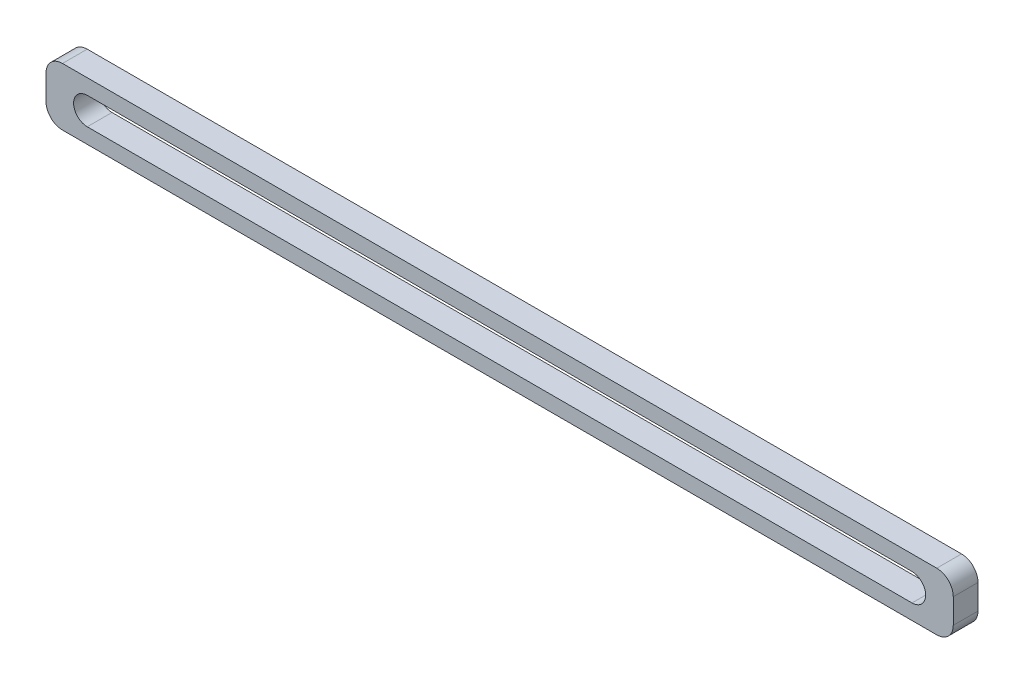
SolidWorks part; units mm, degrees
ref_plane "前视基准面" through (0, 0, 0) normal (0, 0, 1) x (1, 0, 0)
ref_plane "上视基准面" through (0, 0, 0) normal (0, 1, 0) x (1, 0, 0)
ref_plane "右视基准面" through (0, 0, 0) normal (1, 0, 0) x (0, 0, -1)
sketch "草图1" plane through (0, 0, 0) normal (0, 0, 1) x (1, 0, 0)
  line L0 (-50, 0) -> (50, 0) construction
  line L1 (-55, 3.5) -> (55, 3.5)
  line L2 (-55, 3.5) -> (-55, -3.5)
  line L3 (-55, -3.5) -> (55, -3.5)
  line L4 (55, 3.5) -> (55, -3.5)
  line L5 (-55, 3.5) -> (55, -3.5) construction
  line L6 (-55, -3.5) -> (55, 3.5) construction
  line L7 (-50, 1.65) -> (50, 1.65)
  line L8 (-50, -1.65) -> (50, -1.65)
  arc A0 (-50, 1.65) -> (-50, -1.65) centre (-50, 0) ccw
  arc A1 (50, -1.65) -> (50, 1.65) centre (50, 0) ccw
  point P0 (0, 0)
  point P8 (0, 0)
  dimension "D3" = 1.65
  dimension "D1" = 110
  dimension "D2" = 7
  dimension "D4" = 100
extrude "凸台-拉伸1" add sketch "草图1" along normal blind 3
fillet "圆角1" radius 2 4 edges at (-55, 3.5, 1.5) (-55, -3.5, 1.5) (55, -3.5, 1.5) (55, 3.5, 1.5)
